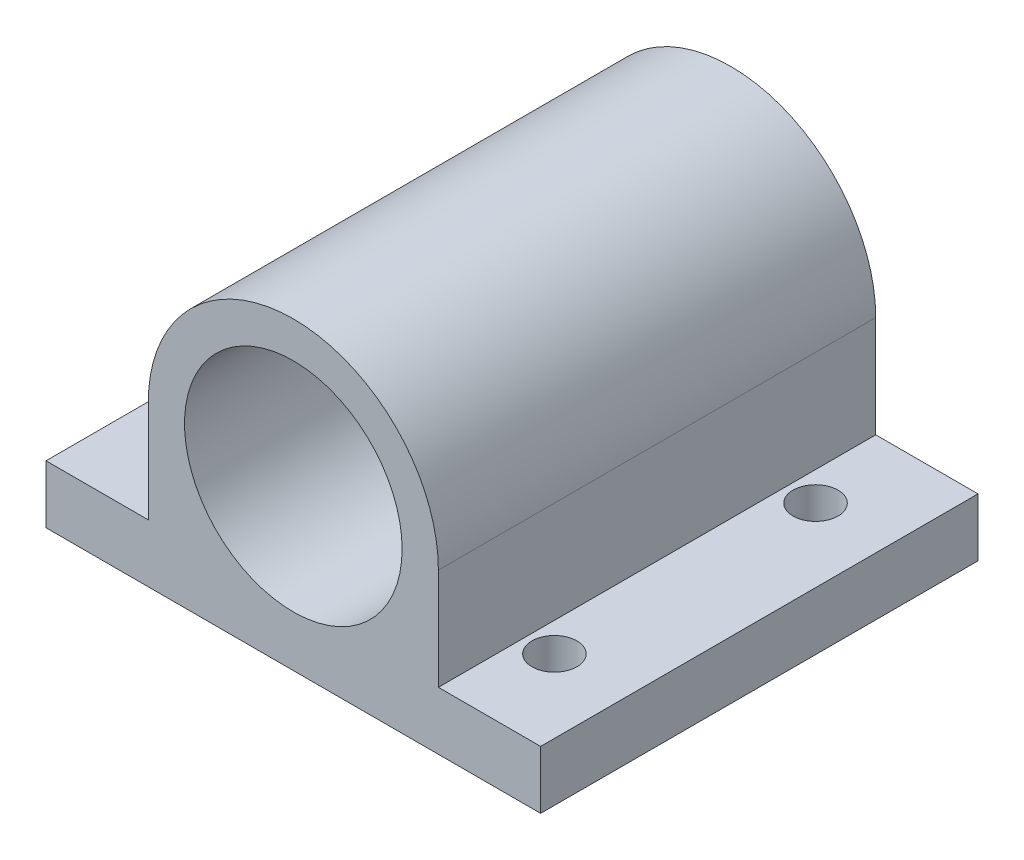
SolidWorks part; units mm, degrees
ref_plane "Front Plane" through (0, 0, 0) normal (0, 0, 1) x (1, 0, 0)
ref_plane "Top Plane" through (0, 0, 0) normal (0, 1, 0) x (1, 0, 0)
ref_plane "Right Plane" through (0, 0, 0) normal (1, 0, 0) x (0, 0, -1)
sketch "Sketch1" plane through (0, 0, 0) normal (0, 0, 1) x (1, 0, 0)
  line L0 (0, 0) -> (-34.1, 0)
  line L1 (-34.1, 0) -> (-34.1, 4)
  line L2 (0, 0) -> (0, 4)
  line L3 (-27.05, 11) -> (-27.05, 4)
  line L4 (-27.05, 4) -> (-34.1, 4)
  line L5 (-7.05, 11) -> (-7.05, 4)
  line L6 (-7.05, 4) -> (0, 4)
  arc A0 (-7.05, 11) -> (-27.05, 11) centre (-17.05, 11) ccw
  circle A1 centre (-17.05, 11) radius 7.5
  point P11 (-17.05, 21)
  dimension "D1" = 15
  dimension "D2" = 20
  dimension "D3" = 34.1
  dimension "D4" = 4
  dimension "D5" = 21
extrude "Boss-Extrude1" add sketch "Sketch1" against normal blind 30.15
sketch "Sketch2" plane through (0, 0, 0) normal (0, -1, 0) x (-1, 0, 0)
  line L0 (34.1, 30.15) -> (34.1, 0) construction
  line L1 (34.1, 0) -> (0, 0) construction
  line L2 (29.05, 6) -> (5.05, 6) construction
  line L3 (29.05, 6) -> (29.05, 24) construction
  line L4 (5.05, 6) -> (5.05, 24) construction
  circle A0 centre (29.05, 6) radius 1.55
  circle A1 centre (29.05, 24) radius 1.55
  circle A2 centre (5.05, 6) radius 1.55
  circle A3 centre (5.05, 24) radius 1.55
  point P6 (0, 0)
  point P12 (9.0882, 26.3822)
  dimension "D1" = 3.1
  dimension "D2" = 5.05
  dimension "D3" = 6
  dimension "D4" = 18
  dimension "D5" = 18
  dimension "D6" = 24
extrude "Cut-Extrude1" cut sketch "Sketch2" against normal blind 30.15
